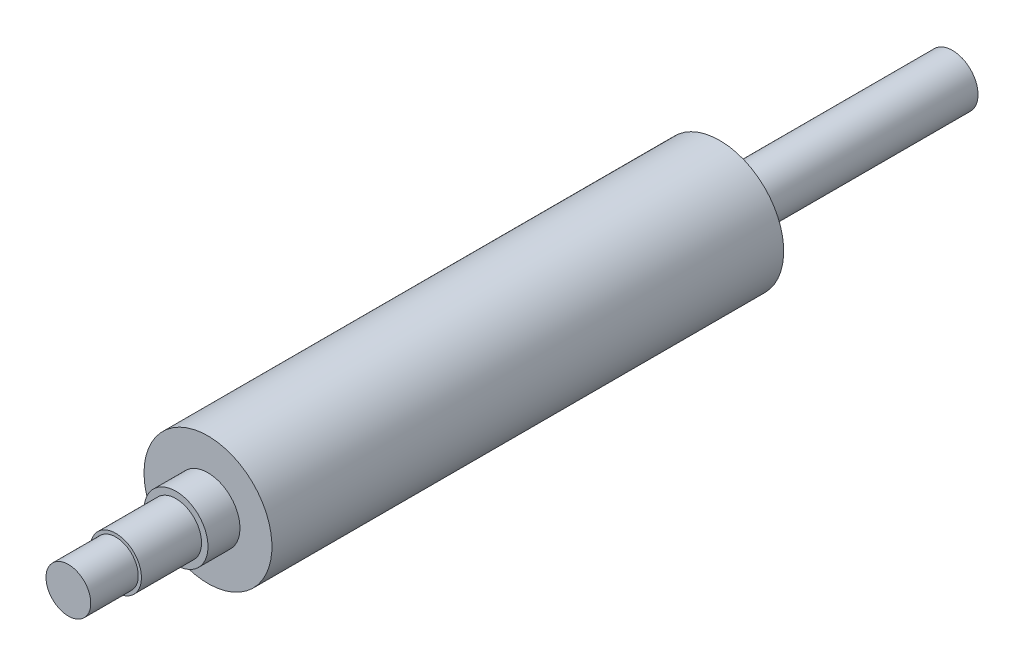
SolidWorks part; units mm, degrees
ref_plane "Ön Düzlem" through (0, 0, 0) normal (0, 0, 1) x (1, 0, 0)
ref_plane "Üst Düzlem" through (0, 0, 0) normal (0, 1, 0) x (1, 0, 0)
ref_plane "Sağ Düzlem" through (0, 0, 0) normal (1, 0, 0) x (0, 0, -1)
sketch "Çizim1" plane through (0, 0, 0) normal (0, 1, 0) x (1, 0, 0)
  line L0 (0, 0) -> (0, -138.2)
  line L1 (0, -138.2) -> (3.5, -138.2)
  line L2 (3.5, -138.2) -> (3.5, -130.78)
  line L3 (3.5, -130.78) -> (4, -130.78)
  line L4 (4, -130.78) -> (4, -121.38)
  line L5 (4, -121.38) -> (5, -121.38)
  line L6 (5, -121.38) -> (5, -116.38)
  line L7 (5, -116.38) -> (10, -116.38)
  line L8 (10, -116.38) -> (10, -36.38)
  line L9 (10, -36.38) -> (5, -36.38)
  line L10 (5, -36.38) -> (5, -32.88)
  line L11 (5, -32.88) -> (4, -32.88)
  line L12 (4, -32.88) -> (4, 0)
  line L13 (4, 0) -> (0, 0)
  dimension "D10" = 5
  dimension "D1" = 138.2
  dimension "D2" = 3.5
  dimension "D3" = 7.42
  dimension "D4" = 4
  dimension "D5" = 9.4
  dimension "D6" = 5
  dimension "D7" = 5
  dimension "D8" = 10
  dimension "D9" = 80
  dimension "D11" = 3.5
  dimension "D12" = 4
revolve "Döndür1" add sketch "Çizim1" angle 360 about L0
